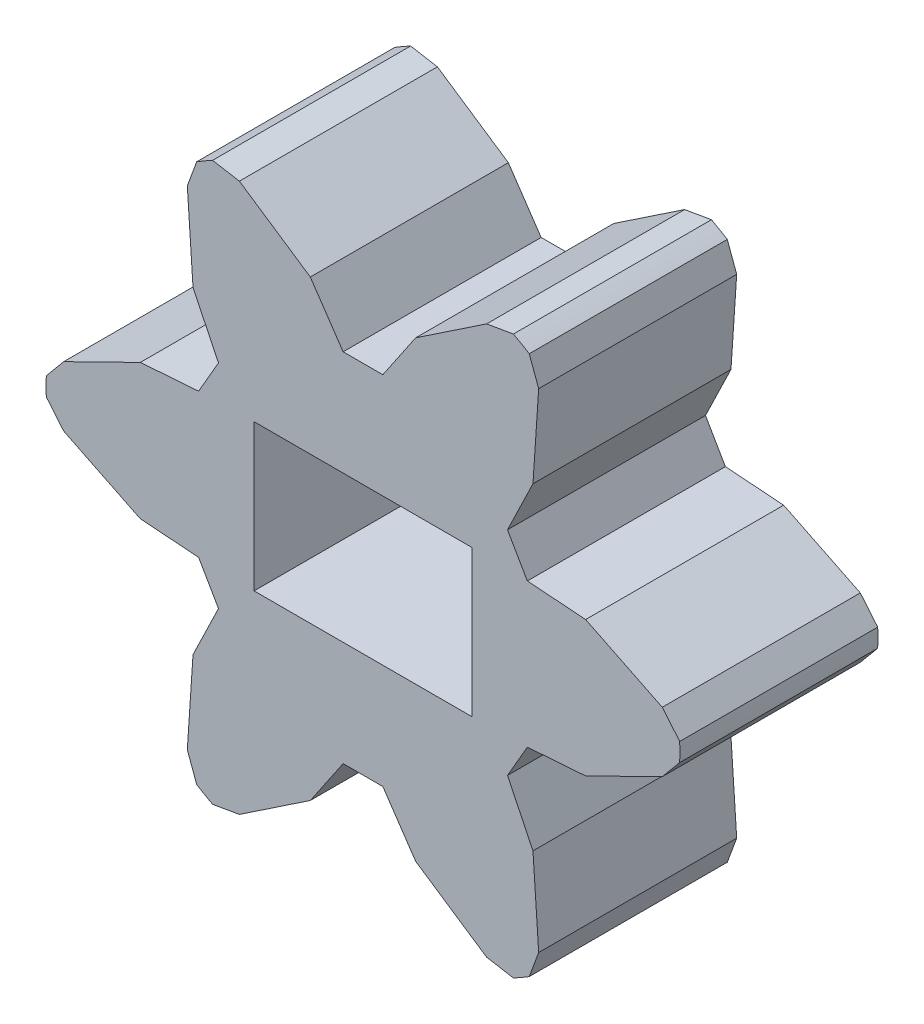
SolidWorks part; units mm, degrees
ref_plane "Front Plane" through (0, 0, 0) normal (0, 0, 1) x (1, 0, 0)
ref_plane "Top Plane" through (0, 0, 0) normal (0, 1, 0) x (1, 0, 0)
ref_plane "Right Plane" through (0, 0, 0) normal (1, 0, 0) x (0, 0, -1)
sketch "Sketch1" plane through (0, 0, 0) normal (0, 0, 1) x (1, 0, 0)
  line L0 (-2.75, 1.85) -> (2.75, 1.85)
  line L1 (1.2374, -1.2374) -> (-1.2374, -1.2374) construction
  line L2 (1.2374, -1.2374) -> (1.2374, 1.2374) construction
  line L3 (1.2374, 1.2374) -> (-1.2374, 1.2374) construction
  line L4 (-1.2374, -1.2374) -> (-1.2374, 1.2374) construction
  line L5 (1.2374, -1.2374) -> (-1.2374, 1.2374) construction
  line L6 (1.2374, 1.2374) -> (-1.2374, -1.2374) construction
  line L7 (2.75, 1.85) -> (2.75, -1.85)
  line L8 (2.75, -1.85) -> (-2.75, -1.85)
  line L9 (-2.75, -1.85) -> (-2.75, 1.85)
  circle A0 centre (0, 0) radius 8
  circle A1 centre (0, 0) radius 1.75 construction
  point P11 (0, 1.85)
  point P13 (-2.75, 0)
  dimension "D1" = 16
  dimension "D2" = 3.5
  dimension "D3" = 5.5
  dimension "D4" = 3.7
extrude "Boss-Extrude1" add sketch "Sketch1" along normal blind 5
sketch "Sketch2" plane through (0, 0, 0) normal (0, 0, 1) x (1, 0, 0)
  line L0 (0, 0) -> (0, 10.088) construction
  line L8 (-7.3319, 22.2218) -> (0, 24.9522)
  line L11 (-1.3301, 5.7236) -> (-3.121, 6.924)
  line L12 (-3.121, 6.924) -> (-3.7984, 7.0407)
  line L13 (-3.7984, 7.0407) -> (-7.3319, 22.2218)
  line L19 (-1.3301, 5.7236) -> (-0.5015, 4.5026)
  line L20 (-0.5015, 4.5026) -> (0.5015, 4.5026)
  line L21 (1.3301, 5.7236) -> (0.5015, 4.5026)
  line L22 (3.7984, 7.0407) -> (7.3319, 22.2218)
  line L23 (3.121, 6.924) -> (3.7984, 7.0407)
  line L24 (1.3301, 5.7236) -> (3.121, 6.924)
  line L25 (7.3319, 22.2218) -> (0, 24.9522)
  circle A14 centre (0, 0) radius 8 construction
  point P9 (0, 4.5026)
  point P16 (0, 8)
  point P18 (-4.5133, 10.7387)
  point P19 (-1.1725, 6.4601)
  point P20 (-5.935, 11.0012)
  point P21 (0, 4.3353)
  point P22 (-0.5698, 4.252)
  point P23 (-0.9863, 5.3184)
  point P24 (-0.5531, 3.8188)
  point P25 (-2.7025, 6.9179)
  point P26 (-1.406, 5.2755)
  point P27 (-3.121, 6.924)
  point P28 (-0.5015, 4.5026)
  point P29 (-1.3301, 5.7236)
extrude "Cut-Extrude1" cut sketch "Sketch2" along normal through all
pattern_circular "CirPattern1" count 6 over 360 about axis through (0, 0, 0) along (0, 0, 1) of "Cut-Extrude1"
sketch "Sketch3" plane through (0, 0, 0) normal (0, 0, 1) x (1, 0, 0)
  circle A0 centre (0, 0) radius 7.5
  dimension "D1" = 15
